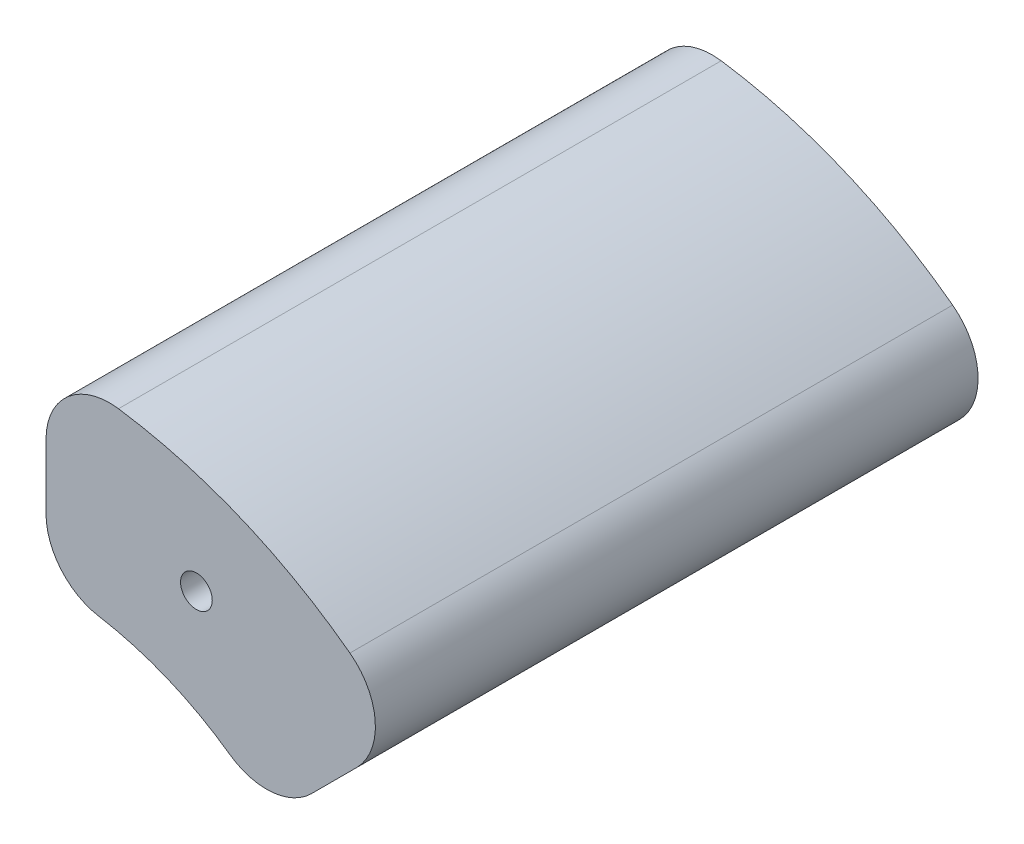
SolidWorks part; units mm, degrees
ref_plane "前视基准面" through (0, 0, 0) normal (0, 0, 1) x (1, 0, 0)
ref_plane "上视基准面" through (0, 0, 0) normal (0, 1, 0) x (1, 0, 0)
ref_plane "右视基准面" through (0, 0, 0) normal (1, 0, 0) x (0, 0, -1)
sketch "草图1" plane through (0, 0, 0) normal (0, 0, 1) x (1, 0, 0)
  line L5 (0, 50) -> (0, 80)
  line L6 (35.3553, 35.3553) -> (56.5685, 56.5685)
  arc A0 (56.5685, 56.5685) -> (0, 80) centre (0, 0) ccw
  arc A1 (35.3553, 35.3553) -> (0, 50) centre (0, 0) ccw
  circle A3 centre (23.7081, 60.4108) radius 2.5
extrude "凸台-拉伸1" add sketch "草图1" along normal blind 95
fillet "圆角1" radius 10 4 edges at (0, 80, 47.5) (56.5685, 56.5685, 47.5) (0, 50, 47.5) (35.3553, 35.3553, 47.5)
